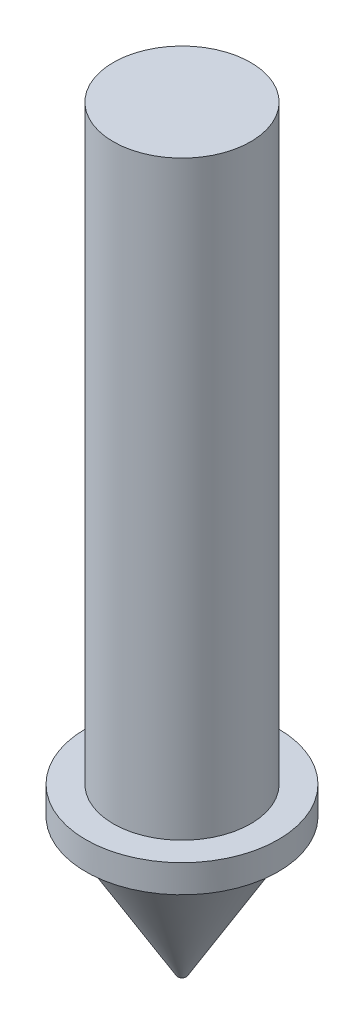
SolidWorks part; units mm, degrees
material "山毛榉"
ref_plane "前视基准面" through (0, 0, 0) normal (0, 0, 1) x (1, 0, 0)
ref_plane "上视基准面" through (0, 0, 0) normal (0, 1, 0) x (1, 0, 0)
ref_plane "右视基准面" through (0, 0, 0) normal (1, 0, 0) x (0, 0, -1)
sketch "草图1" plane through (0, 0, 0) normal (0, 1, 0) x (1, 0, 0)
  circle A0 centre (0, 0) radius 7
extrude "凸台-拉伸1" add sketch "草图1" along normal blind 55
sketch "草图2" plane through (0, 55, 0) normal (0, 1, 0) x (1, 0, 0)
  circle A0 centre (0, 0) radius 5
  circle M2 centre (0, 0) radius 7
extrude "切除-拉伸2" cut sketch "草图2" against normal blind 43 contours A0 M2
sketch "草图8" plane through (0, 0, 0) normal (0, 0, 1) x (1, 0, 0)
  line L0 (0, 0) -> (0, 12.2388) construction
  line L1 (-7, 9.9745) -> (-6.2319, 9.9745)
  line L2 (-0.3079, 0) -> (-7, 0)
  line L3 (-7, 0) -> (-7, 9.9745)
  line L4 (-7, 12) -> (-7, 0) construction
  line L5 (-6.2319, 9.9745) -> (-0.3079, 0)
revolve "切除-旋转25" cut sketch "草图8" angle 360 about L0
